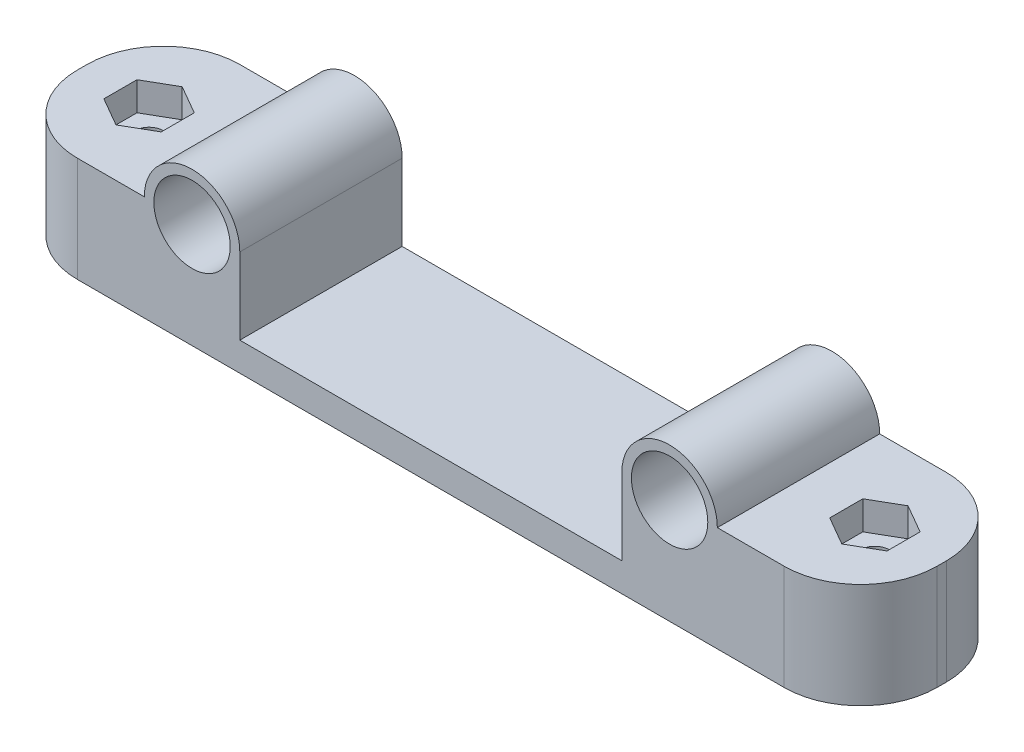
SolidWorks part; units mm, degrees
ref_plane "Front Plane" through (0, 0, 0) normal (0, 0, 1) x (1, 0, 0)
ref_plane "Top Plane" through (0, 0, 0) normal (0, 1, 0) x (1, 0, 0)
ref_plane "Right Plane" through (0, 0, 0) normal (1, 0, 0) x (0, 0, -1)
sketch "Sketch1" plane through (0, 0, 0) normal (0, 0, 1) x (1, 0, 0)
  line L0 (-45, 0) -> (45, 0)
  line L1 (30, 11) -> (45, 11)
  line L2 (45, 11) -> (45, 0)
  line L4 (0, 3) -> (0, 0) construction
  line L5 (-45, 11) -> (-45, 0)
  line L6 (-30, 11) -> (-45, 11)
  line L7 (-20, 11) -> (-20, 3)
  line L8 (-20, 3) -> (20, 3)
  line L9 (20, 3) -> (20, 11)
  arc A0 (30, 11) -> (20, 11) centre (25, 11) ccw
  arc A1 (-30, 11) -> (-20, 11) centre (-25, 11) cw
  circle A2 centre (25, 11) radius 4
  circle A3 centre (-25, 11) radius 4
  dimension "D3" = 8
  dimension "D4" = 5
  dimension "D1" = 50
  dimension "D2" = 11
  dimension "D5" = 3
  dimension "D6" = 15
extrude "Boss-Extrude1" add sketch "Sketch1" along normal blind 15
sketch "Sketch2" plane through (0, 0, 0) normal (0, 0, -1) x (-1, 0, 0)
  line L8 (-45, 11) -> (-45, 0)
  line L9 (-45, 0) -> (45, 0)
  line L10 (45, 0) -> (45, 11)
  line L11 (45, 11) -> (30, 11)
  line L12 (20, 11) -> (20, 3)
  line L13 (20, 3) -> (-20, 3)
  line L14 (-20, 3) -> (-20, 11)
  line L15 (-30, 11) -> (-45, 11)
  line L16 (-45, 11) -> (-45, 0)
  line L17 (-45, 0) -> (45, 0)
  line L18 (45, 0) -> (45, 11)
  line L19 (45, 11) -> (30, 11)
  line L20 (20, 11) -> (20, 3)
  line L21 (20, 3) -> (-20, 3)
  line L22 (-20, 3) -> (-20, 11)
  line L23 (-30, 11) -> (-45, 11)
  arc A2 (30, 11) -> (20, 11) centre (25, 11) ccw
  arc A3 (-20, 11) -> (-30, 11) centre (-25, 11) ccw
  arc A4 (30, 11) -> (20, 11) centre (25, 11) ccw
  arc A5 (-20, 11) -> (-30, 11) centre (-25, 11) ccw
  dimension "D1" = 0
extrude "Boss-Extrude2" add sketch "Sketch2" along normal blind 2
sketch "Sketch3" plane through (0, 11, 0) normal (0, 1, 0) x (1, 0, 0)
  line L0 (45, -15) -> (45, 2) construction
  line L1 (0, -55) -> (0, 55) construction
  circle A0 centre (38, -6.5) radius 1.5
  point P7 (45, -6.5)
  dimension "D1" = 3
  dimension "D2" = 38
extrude "Cut-Extrude1" cut sketch "Sketch3" against normal through all
mirror "Mirror1" about plane through (0, 0, 0) normal (1, 0, 0) of "Cut-Extrude1"
fillet "Fillet1" radius 8 4 edges at (-45, 5.5, 15) (-45, 5.5, -2) (45, 5.5, -2) (45, 5.5, 15)
sketch "Sketch4" plane through (0, 11, 0) normal (0, 1, 0) x (1, 0, 0)
  line L8 (38, -3.0359) -> (35, -4.7679)
  line L9 (35, -4.7679) -> (35, -8.2321)
  line L10 (35, -8.2321) -> (38, -9.9641)
  line L11 (38, -9.9641) -> (41, -8.2321)
  line L12 (41, -8.2321) -> (41, -4.7679)
  line L13 (41, -4.7679) -> (38, -3.0359)
  circle A0 centre (38, -6.5) radius 3 construction
  dimension "D1" = 6
extrude "Cut-Extrude2" cut sketch "Sketch4" against normal blind 3
mirror "Mirror3" about plane through (0, 0, 0) normal (1, 0, 0) of "Cut-Extrude2"
